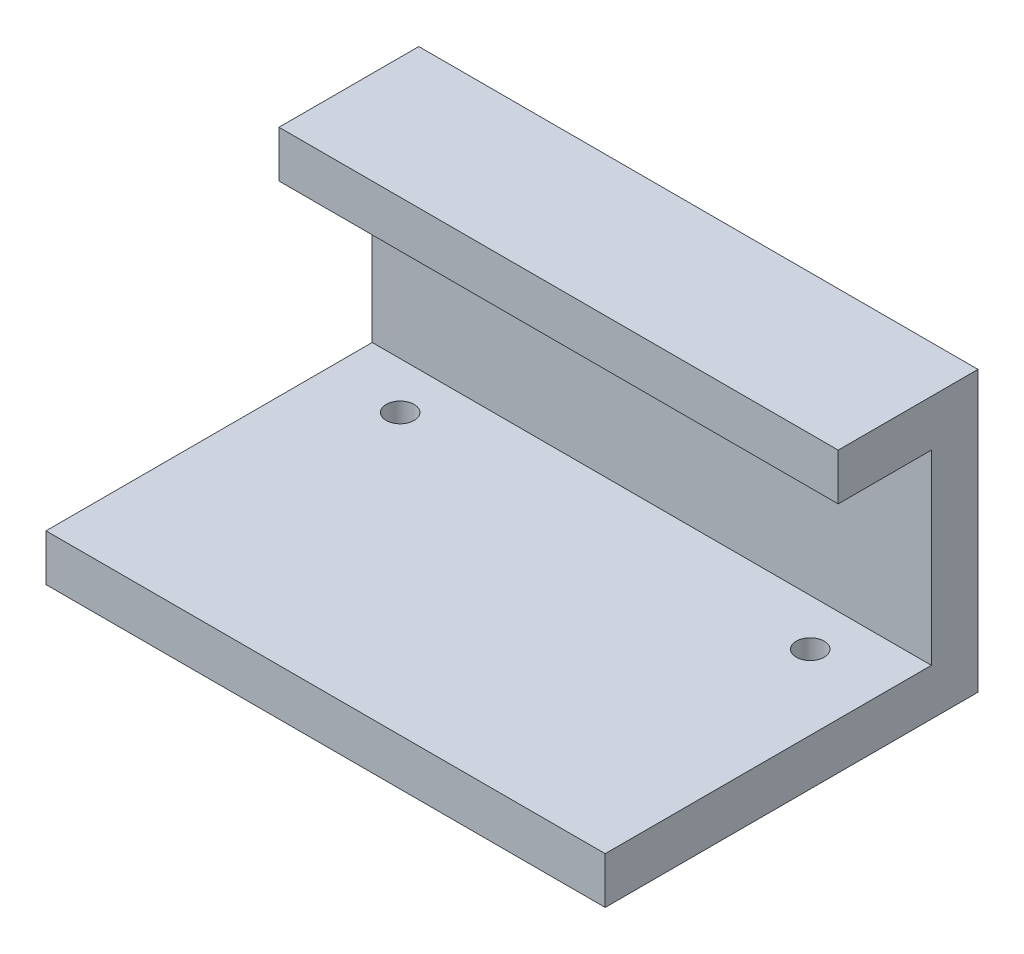
SolidWorks part; units mm, degrees
ref_plane "Спереди" through (0, 0, 0) normal (0, 0, 1) x (1, 0, 0)
ref_plane "Сверху" through (0, 0, 0) normal (0, 1, 0) x (1, 0, 0)
ref_plane "Справа" through (0, 0, 0) normal (1, 0, 0) x (0, 0, -1)
sketch "Эскиз1" plane through (0, 0, 0) normal (0, 1, 0) x (1, 0, 0)
  line L1 (30, -20) -> (-30, -20)
  line L2 (30, -20) -> (30, 20)
  line L3 (30, 20) -> (-30, 20)
  line L4 (-30, -20) -> (-30, 20)
  line L5 (30, -20) -> (-30, 20) construction
  line L6 (30, 20) -> (-30, -20) construction
  point P0 (0, 0)
  dimension "D1" = 60
  dimension "D2" = 40
sketch "Эскиз2" plane through (0, 0, 0) normal (0, 1, 0) x (1, 0, 0)
extrude "Бобышка-Вытянуть1" add sketch "Эскиз1" along normal blind 5
sketch "Эскиз3" plane through (0, 5, 0) normal (0, 1, 0) x (1, 0, 0)
  line L0 (30, -20) -> (30, 20) construction
  line L1 (-30, 20) -> (30, 20)
  line L2 (-30, 20) -> (-30, 15)
  line L3 (-30, 15) -> (30, 15)
  line L4 (30, 20) -> (30, 15)
  dimension "D1" = 5
extrude "Бобышка-Вытянуть2" add sketch "Эскиз3" along normal blind 25
sketch "Эскиз4" plane through (0, 0, -15) normal (0, 0, 1) x (1, 0, 0)
  line L0 (-30, 30) -> (-30, 5) construction
  line L1 (30, 30) -> (-30, 30)
  line L2 (30, 30) -> (30, 25)
  line L3 (30, 25) -> (-30, 25)
  line L4 (-30, 30) -> (-30, 25)
  dimension "D1" = 5
extrude "Бобышка-Вытянуть3" add sketch "Эскиз4" along normal blind 10
sketch "Эскиз5" plane through (0, 0, 0) normal (0, -1, 0) x (1, 0, 0)
  line L0 (22, -10) -> (-22, -10) construction
  line L1 (30, -20) -> (-30, -20) construction
  line L2 (30, 20) -> (30, -20) construction
  circle A0 centre (22, -10) radius 1.5
  circle A1 centre (-22, -10) radius 1.5
  dimension "D4" = 3
  dimension "D5" = 3
  dimension "D1" = 44
  dimension "D2" = 10
  dimension "D3" = 8
extrude "Вырез-Вытянуть1" cut sketch "Эскиз5" against normal blind 5
